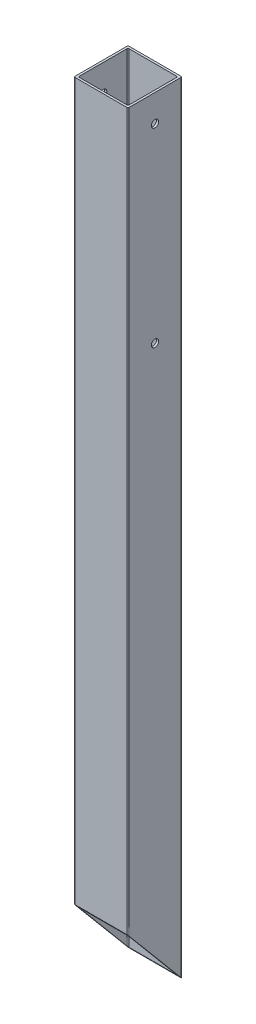
SolidWorks part; units mm, degrees
ref_plane "Plan de face" through (0, 0, 0) normal (0, 0, 1) x (1, 0, 0)
ref_plane "Plan de dessus" through (0, 0, 0) normal (0, 1, 0) x (1, 0, 0)
ref_plane "Plan de droite" through (0, 0, 0) normal (1, 0, 0) x (0, 0, -1)
sketch "Esquisse2" plane through (0, 0, 0) normal (0, 1, 0) x (1, 0, 0)
  line L0 (6, 96) -> (94, 96)
  line L1 (2, 0) -> (98, 0)
  line L2 (0, 2) -> (0, 98)
  line L3 (2, 100) -> (98, 100)
  line L4 (100, 2) -> (100, 98)
  line L5 (96, 6) -> (96, 94)
  line L6 (6, 4) -> (94, 4)
  line L7 (4, 6) -> (4, 94)
  line L8 (4, 4) -> (4, 96) construction
  line L9 (4, 96) -> (96, 96) construction
  line L10 (96, 4) -> (96, 96) construction
  line L11 (4, 4) -> (96, 4) construction
  line L12 (0, 0) -> (0, 100) construction
  line L13 (0, 0) -> (100, 0) construction
  line L14 (100, 0) -> (100, 100) construction
  line L15 (0, 100) -> (100, 100) construction
  arc A0 (4, 94) -> (6, 96) centre (6, 94) cw
  arc A1 (96, 6) -> (94, 4) centre (94, 6) cw
  arc A2 (6, 4) -> (4, 6) centre (6, 6) cw
  arc A3 (0, 2) -> (2, 0) centre (2, 2) ccw
  arc A4 (98, 0) -> (100, 2) centre (98, 2) ccw
  arc A5 (96, 94) -> (94, 96) centre (94, 94) ccw
  arc A6 (100, 98) -> (98, 100) centre (98, 98) ccw
  arc A7 (2, 100) -> (0, 98) centre (2, 98) ccw
  point P21 (0, 0)
  dimension "D4" = 2
  dimension "D1" = 100
  dimension "D2" = 100
  dimension "D3" = 4
extrude "Boss.-Extru.1" add sketch "Esquisse2" along normal blind 1500
sketch "Esquisse4" plane through (0, 0, 0) normal (-1, 0, 0) x (0, 0, 1)
  line L0 (-50, 1098) -> (-50, 1450) construction
  line L1 (-98, 1500) -> (-2, 1500) construction
  line L2 (-50, 174) -> (-50, 1098) construction
  line L3 (-50, 1450) -> (-50, 1500) construction
  line L4 (0, 124) -> (-100, 124) construction
  line L5 (-100, 1500) -> (-100, 0) construction
  line L6 (0, 1500) -> (0, 0) construction
  line L7 (-50, 174) -> (0, 174) construction
  line L8 (0, 174) -> (-165.4645, -23.193)
  line L13 (-165.4645, -23.193) -> (56.2659, -23.193)
  line L14 (56.2659, -23.193) -> (56.2659, 174)
  line L15 (56.2659, 174) -> (0, 174)
  circle A0 centre (-50, 1450) radius 6.75
  circle A1 centre (-50, 1098) radius 6.75
  circle A2 centre (-50, 174) radius 15 construction
  circle A3 centre (-50, 174) radius 50 construction
  point P4 (-50, 1274)
  point P15 (0, 174)
  point P22 (-50, 124)
  dimension "D2" = 13.5
  dimension "D3" = 13.5
  dimension "D4" = 50
  dimension "D6" = 30
  dimension "D1" = 352
  dimension "D5" = 1100
  dimension "D7" = 40
extrude "Enlèv. mat.-Extru.1" cut sketch "Esquisse4" against normal through all
